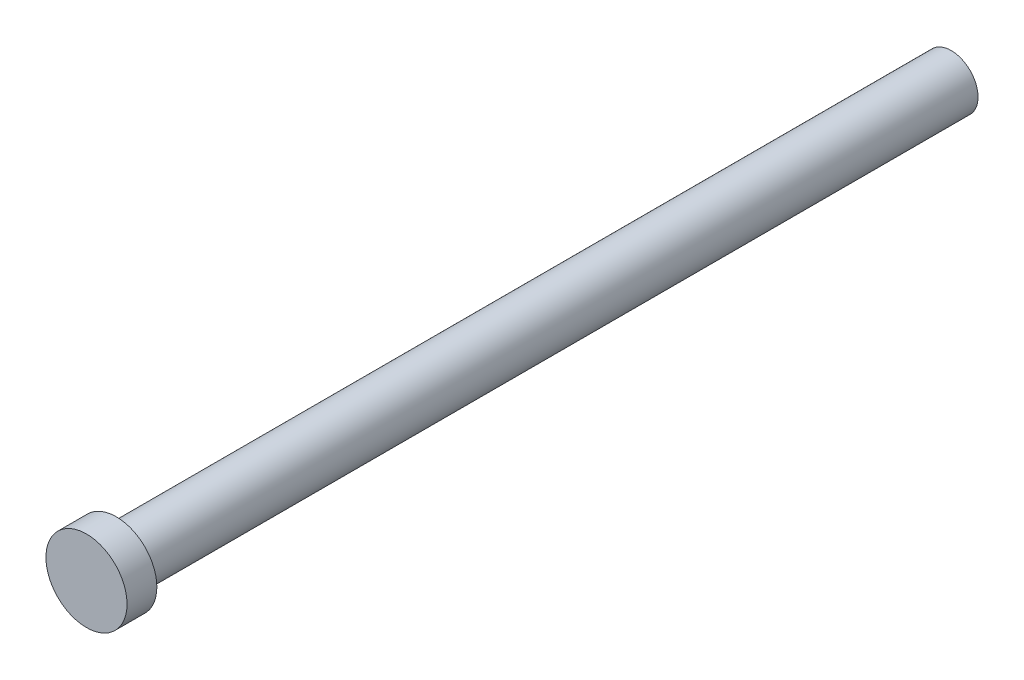
SolidWorks part; units mm, degrees
ref_plane "Plan de face" through (0, 0, 0) normal (0, 0, 1) x (1, 0, 0)
ref_plane "Plan de dessus" through (0, 0, 0) normal (0, 1, 0) x (1, 0, 0)
ref_plane "Plan de droite" through (0, 0, 0) normal (1, 0, 0) x (0, 0, -1)
sketch "Esquisse1" plane through (0, 0, 0) normal (0, 0, 1) x (1, 0, 0)
  circle A0 centre (0, 0) radius 1.7
extrude "Boss.-Extru.1" add sketch "Esquisse1" along normal blind 1.25
sketch "Esquisse2" plane through (0, 0, 0) normal (0, 0, -1) x (-1, 0, 0)
  circle A0 centre (0, 0) radius 1.125
extrude "Boss.-Extru.2" add sketch "Esquisse2" along normal blind 35
